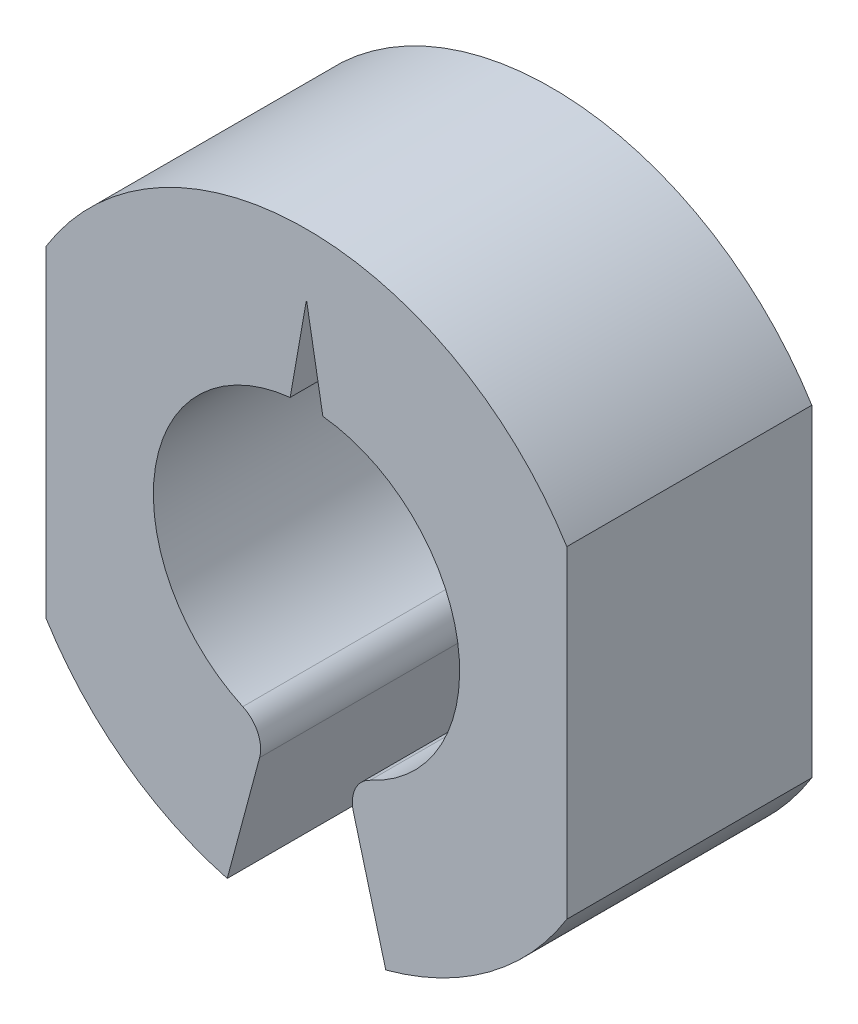
SolidWorks part; units mm, degrees
ref_plane "前视基准面" through (0, 0, 0) normal (0, 0, 1) x (1, 0, 0)
ref_plane "上视基准面" through (0, 0, 0) normal (0, 1, 0) x (1, 0, 0)
ref_plane "右视基准面" through (0, 0, 0) normal (1, 0, 0) x (0, 0, -1)
sketch "草图1" plane through (0, 0, 0) normal (0, 0, 1) x (1, 0, 0)
  line L0 (0, 0) -> (0, -9) construction
  line L1 (0, 0) -> (2.5882, -9.6593) construction
  line L2 (0, 0) -> (-2.5882, -9.6593) construction
  line L3 (1.2941, -4.8296) -> (2.5882, -9.6593)
  line L4 (-2.5882, -9.6593) -> (-1.2941, -4.8296)
  arc A0 (1.2941, -4.8296) -> (-1.2941, -4.8296) centre (0, 0) ccw
  arc A1 (2.5882, -9.6593) -> (-2.5882, -9.6593) centre (0, 0) ccw
  dimension "D1" = 10
  dimension "D2" = 20
  dimension "D3" = 15
  dimension "D4" = 15
extrude "凸台-拉伸1" add sketch "草图1" along normal blind 8
fillet "圆角1" radius 1 2 edges at (-1.2941, -4.8296, 4) (1.2941, -4.8296, 4)
sketch "草图2" plane through (0, 0, 8) normal (0, 0, 1) x (1, 0, 0)
  line L0 (-8.5, 5.2678) -> (-8.5, -5.2678)
  line L1 (8.5, 5.2678) -> (8.5, -5.2678)
  arc A0 (2.5882, -9.6593) -> (-2.5882, -9.6593) centre (0, 0) ccw construction
  arc A1 (8.5, -5.2678) -> (8.5, 5.2678) centre (0, 0) ccw
  arc A2 (-8.5, 5.2678) -> (-8.5, -5.2678) centre (0, 0) ccw
  dimension "D1" = 8.5
  dimension "D2" = 8.5
extrude "切除-拉伸1" cut sketch "草图2" against normal blind 10
sketch "草图3" plane through (0, 0, 0) normal (0, 0, -1) x (-1, 0, 0)
  line L0 (0, 10) -> (0, 8) construction
  line L1 (0, 8) -> (-0.534, 4.9714)
  line L2 (0, 8) -> (0.534, 4.9714)
  arc A0 (2.0809, -4.5464) -> (-2.0809, -4.5464) centre (0, 0) ccw construction
  arc A1 (0.534, 4.9714) -> (-0.534, 4.9714) centre (0, 0) ccw
  arc A2 (8.5, 5.2678) -> (-8.5, 5.2678) centre (0, 0) ccw construction
  dimension "D1" = 2
  dimension "D2" = 170
  dimension "D3" = 170
extrude "切除-拉伸2" cut sketch "草图3" against normal through all
